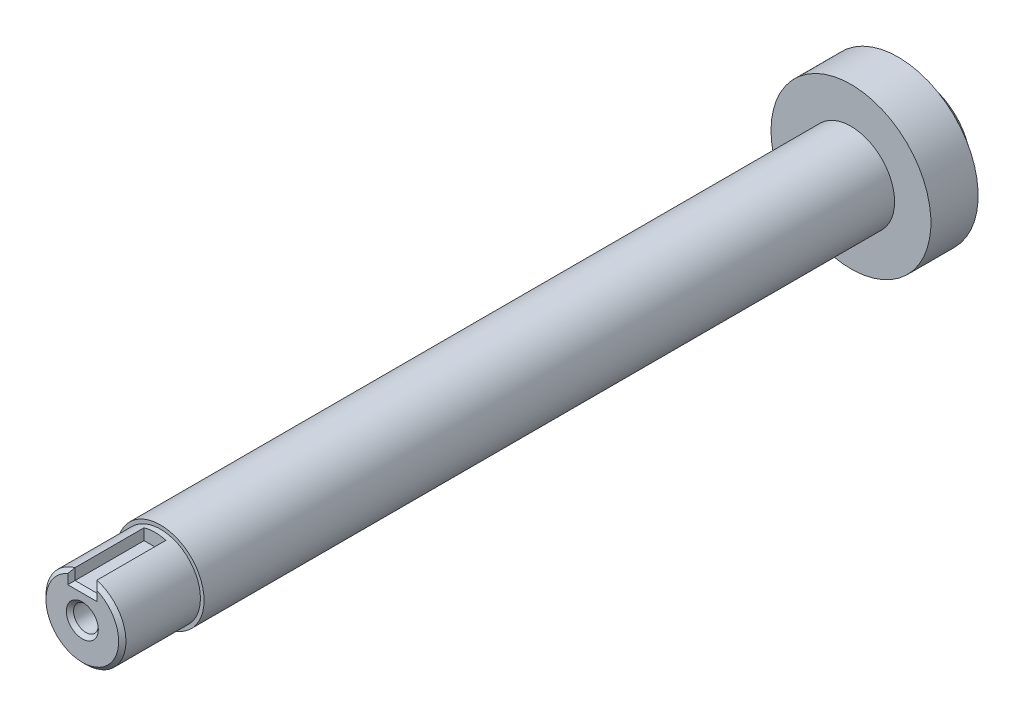
SolidWorks part; units mm, degrees
material "1.7225 (42CrMo4)"
ref_plane "Front Plane" through (0, 0, 0) normal (0, 0, 1) x (1, 0, 0)
ref_plane "Top Plane" through (0, 0, 0) normal (0, 1, 0) x (1, 0, 0)
ref_plane "Right Plane" through (0, 0, 0) normal (1, 0, 0) x (0, 0, -1)
ref_plane "Plane1" through (0, 0, 0) normal (0, -1, 0) x (1, 0, 0)
sketch "Sketch1" plane through (0, 0, 0) normal (0, -1, 0) x (1, 0, 0)
  line L0 (22, 19) -> (0, 19)
  line L1 (0, 19) -> (0, 6)
  line L2 (0, 6) -> (22, 6)
  line L3 (22, 6) -> (22, 19)
  line L4 (0, 19) -> (0, 6) construction
  dimension "D1" = 22
  dimension "D2" = 13
  dimension "D3" = 22
  dimension "D4" = 19
revolve "Revolve1" add sketch "Sketch1" angle 360 about L4
sketch "Sketch2" plane through (0, 0, 19) normal (0, 0, 1) x (1, 0, 0)
  circle A0 centre (0, 0) radius 12
  dimension "D1" = 24
extrude "Boss-Extrude1" add sketch "Sketch2" along normal blind 190
sketch "Sketch3" plane through (0, 0, 209) normal (0, 0, 1) x (1, 0, 0)
  circle A0 centre (0, 0) radius 11
  dimension "D1" = 22
extrude "Boss-Extrude2" add sketch "Sketch3" along normal blind 21.5
sketch "Sketch4" plane through (0, 0, 230.5) normal (0, 0, 1) x (1, 0, 0)
  line L0 (3, 7.5) -> (3, 10.583)
  line L1 (-3, 10.583) -> (-3, 7.5)
  line L2 (-3, 7.5) -> (3, 7.5)
  arc A0 (3, 10.583) -> (-3, 10.583) centre (0, 0) ccw
  circle A1 centre (0, 0) radius 11 construction
  dimension "D1" = 11
  dimension "D2" = 3
  dimension "D3" = 3
  dimension "D4" = 7.5
  dimension "D5" = 10.583
extrude "Cut-Extrude1" cut sketch "Sketch4" against normal blind 20
sketch "Sketch5" plane through (0, 0, 6) normal (0, 0, -1) x (-1, 0, 0)
  circle A0 centre (0, 0) radius 15
  dimension "D1" = 30
extrude "Boss-Extrude3" add sketch "Sketch5" along normal blind 6
hole_wizard "Ø6.8 (6.8) Diameter Hole1" positions "Sketch7" profile "Sketch6" hole size "Ø6.8" standard "ANSI Metric"
sketch "Sketch7" plane through (0, 0, 230.5) normal (0, 0, 1) x (1, 0, 0)
  point P0 (0, 0)
sketch "Sketch6" plane through (0, 0, 230.5) normal (1, 0, 0) x (0, -1, 0)
  line L0 (0, 0) -> (0, 16)
  line L1 (0, 16) -> (3.4, 16)
  line L2 (3.4, 16) -> (3.4, 0)
  line L5 (3.4, 0) -> (0, 0)
  line L10 (0, 16) -> (-3.4, 16) construction
  line L11 (0, -6.35) -> (0, 107.95) construction
  dimension "Hole Dia." = 6.8
  dimension "Hole Depth" = 16
  dimension "Drill Angle" = 180
chamfer "Chamfer1" distance 1 angle 45 6 edges at (3, 9.0415, 230.5) (0, 7.5, 230.5) (0, -11, 230.5) (-3, 9.0415, 230.5) (0, 15, 0) (3.4, 0, 230.5)
